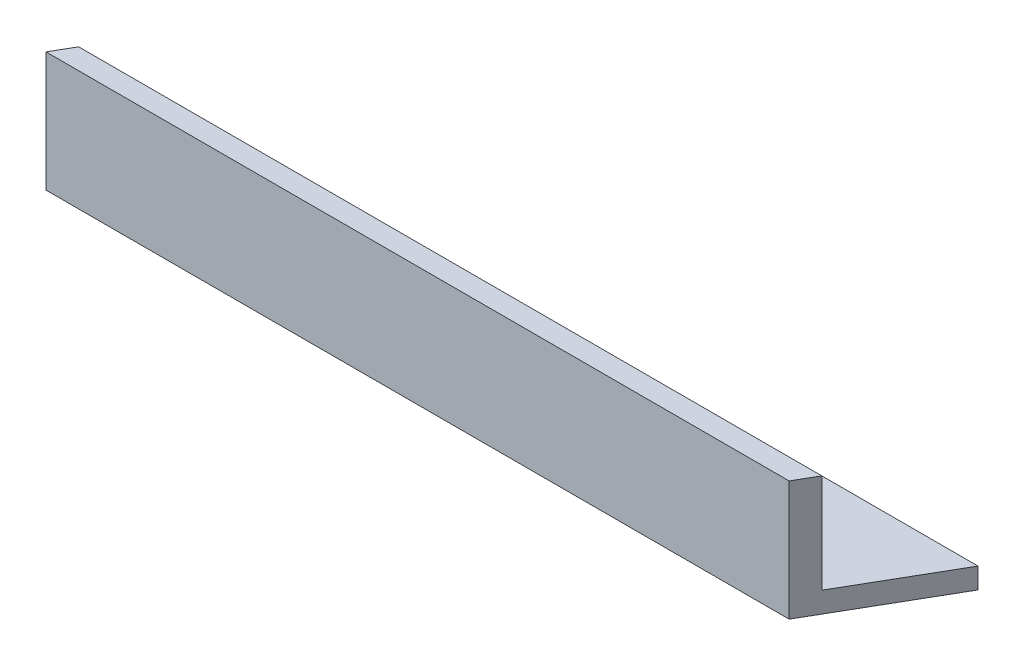
SolidWorks part; units mm, degrees
ref_plane "Front Plane" through (0, 0, 0) normal (0, 0, 1) x (1, 0, 0)
ref_plane "Top Plane" through (0, 0, 0) normal (0, 1, 0) x (1, 0, 0)
ref_plane "Right Plane" through (0, 0, 0) normal (1, 0, 0) x (0, 0, -1)
sketch "Sketch1" plane through (0, 0, 0) normal (1, 0, 0) x (0, 0, -1)
  line L0 (0, 0) -> (20, 0)
  line L1 (20, 0) -> (20, 3.4612)
  line L2 (20, 3.4612) -> (3.4612, 3.4612)
  line L3 (3.4612, 3.4612) -> (3.4612, 20)
  line L4 (3.4612, 20) -> (0, 20)
  line L5 (0, 20) -> (0, 0)
  dimension "D1" = 3.4612
  dimension "D2" = 20
extrude "Boss-Extrude1" add sketch "Sketch1" along normal blind 240
sketch "Sketch2" plane through (0, 0, 0) normal (0, -1, 0) x (1, 0, 0)
  line L0 (0, 0) -> (11.547, -20)
  line L1 (240, -20) -> (0, -20) construction
  line L2 (11.547, -20) -> (0, -20)
  line L3 (0, -20) -> (0, 0)
  line L4 (240, 0) -> (240, -20)
  line L5 (240, -20) -> (135.6773, -20)
  line L6 (135.6773, -20) -> (124.1303, 0)
  line L7 (240, 0) -> (0, 0) construction
  line L8 (124.1303, 0) -> (240, 0)
  dimension "D1" = 30
  dimension "D2" = 107.5
extrude "Cut-Extrude1" cut sketch "Sketch2" against normal through all
